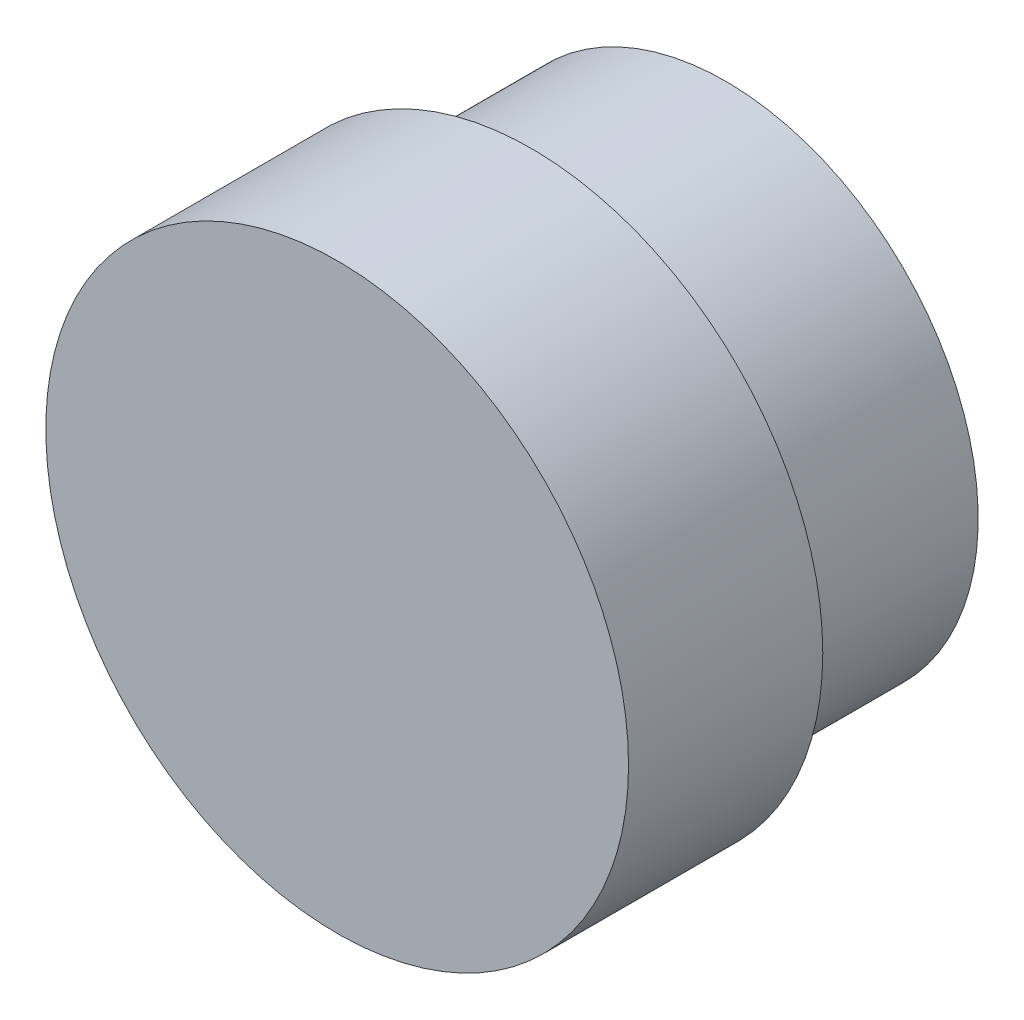
SolidWorks part; units mm, degrees
ref_plane "正面" through (0, 0, 0) normal (0, 0, 1) x (1, 0, 0)
ref_plane "平面" through (0, 0, 0) normal (0, 1, 0) x (1, 0, 0)
ref_plane "右側面" through (0, 0, 0) normal (1, 0, 0) x (0, 0, -1)
sketch "ｽｹｯﾁ5" plane through (0, 0, 0) normal (0, 1, 0) x (1, 0, 0)
  line L0 (0, -50) -> (0, -55)
  line L1 (-6.5, -55) -> (6.5, -55)
  line L2 (-6.5, -55) -> (-6.5, -50)
  line L3 (-6.5, -50) -> (6.5, -50)
  line L4 (6.5, -55) -> (6.5, -50)
  line L5 (-6.5, -55) -> (6.5, -50) construction
  line L6 (-6.5, -50) -> (6.5, -55) construction
  point P0 (0, -52.5)
  dimension "D1" = 52.5
  dimension "D2" = 13
  dimension "D3" = 5
revolve "回転4" add sketch "ｽｹｯﾁ5" angle 360 about L0
sketch "ｽｹｯﾁ7" plane through (0, 0, 0) normal (0, 1, 0) x (1, 0, 0)
  line L0 (0, -60) -> (0, -55) construction
  line L1 (-7.5, -60) -> (7.5, -60)
  line L2 (-7.5, -60) -> (-7.5, -55)
  line L3 (-7.5, -55) -> (7.5, -55)
  line L4 (7.5, -60) -> (7.5, -55)
  point P0 (0, -57.5)
  dimension "D1" = 57.5
  dimension "D2" = 5
  dimension "D3" = 15
revolve "回転5" add sketch "ｽｹｯﾁ7" angle 360 about L0
